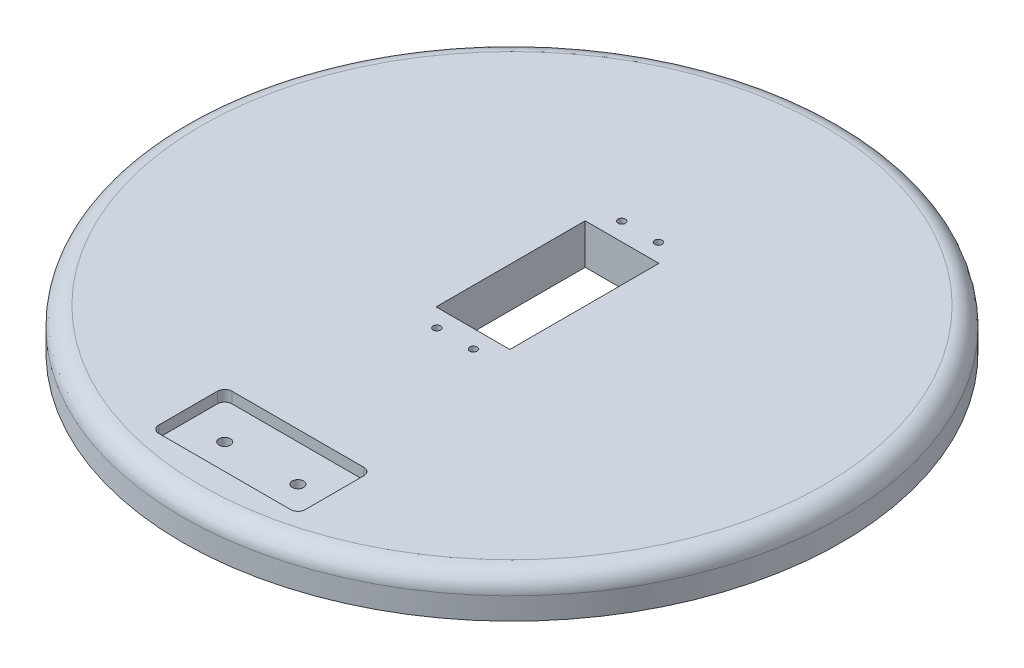
SolidWorks part; units mm, degrees
ref_plane "Front Plane" through (0, 0, 0) normal (0, 0, 1) x (1, 0, 0)
ref_plane "Top Plane" through (0, 0, 0) normal (0, 1, 0) x (1, 0, 0)
ref_plane "Right Plane" through (0, 0, 0) normal (1, 0, 0) x (0, 0, -1)
sketch "Sketch1" plane through (0, 0, 0) normal (0, 1, 0) x (1, 0, 0)
  circle A0 centre (0, 0) radius 90
  dimension "D1" = 180
extrude "Boss-Extrude1" add sketch "Sketch1" along normal blind 11
sketch "Sketch7" plane through (0, 11, 0) normal (0, 1, 0) x (1, 0, 0)
  line L1 (-20, -58.4613) -> (20, -58.4613)
  line L2 (-20, -58.4613) -> (-20, -78.4613)
  line L3 (-20, -78.4613) -> (20, -78.4613)
  line L4 (20, -58.4613) -> (20, -78.4613)
  dimension "D2" = 40
  dimension "D1" = 20
extrude "Cut-Extrude7" cut sketch "Sketch7" against normal blind 3
sketch "Sketch12" plane through (0, 8, 0) normal (0, 1, 0) x (1, 0, 0)
  circle A0 centre (10, -68.4613) radius 1.55
  circle A1 centre (-10, -68.4613) radius 1.55
  dimension "D1" = 3.1
  dimension "D2" = 3.1
extrude "Cut-Extrude8" cut sketch "Sketch12" against normal blind 20
sketch "Sketch13" plane through (0, 0, 0) normal (0, -1, 0) x (1, 0, 0)
  circle A0 centre (10, 68.4613) radius 3
  circle A1 centre (-10, 68.4613) radius 3
  dimension "D1" = 6
  dimension "D2" = 6
extrude "Cut-Extrude9" cut sketch "Sketch13" against normal blind 3
fillet "Fillet1" radius 2 1 edges at (-20, 9.5, 58.4613)
fillet "Fillet2" radius 2 1 edges at (20, 9.5, 58.4613)
fillet "Fillet3" radius 2 1 edges at (-20, 9.5, 78.4613)
fillet "Fillet4" radius 2 1 edges at (20, 9.5, 78.4613)
sketch "Sketch15" plane through (0, 0, 0) normal (0, -1, 0) x (1, 0, 0)
  circle A0 centre (0, 0) radius 75.2
  circle A1 centre (0, 0) radius 85.2
  circle A2 centre (0, 0) radius 90 construction
  dimension "D1" = 4.8
  dimension "D2" = 10
extrude "Cut-Extrude10" cut sketch "Sketch15" against normal blind 6
fillet "Fillet5" radius 5 1 edges at (0, 11, 90)
sketch "Sketch16" plane through (0, 11, 0) normal (0, 1, 0) x (1, 0, 0)
  line L1 (10.0705, -10.6552) -> (-10.0693, -10.6552)
  line L2 (10.0705, -10.6552) -> (10.0705, 30.0651)
  line L3 (10.0705, 30.0651) -> (-10.0693, 30.0651)
  line L4 (-10.0693, -10.6552) -> (-10.0693, 30.0651)
extrude "Cut-Extrude13" cut sketch "Sketch16" against normal blind 20
sketch "Sketch17" plane through (0, 11, 0) normal (0, 1, 0) x (1, 0, 0)
  circle A0 centre (-5, 34.9655) radius 1
  circle A1 centre (5, 34.9655) radius 1
  circle A2 centre (-5, -15.5345) radius 1
  circle A3 centre (5, -15.5345) radius 1
  dimension "D1" = 2
  dimension "D2" = 2
  dimension "D3" = 2
  dimension "D4" = 2
extrude "Cut-Extrude14" cut sketch "Sketch17" against normal blind 10
